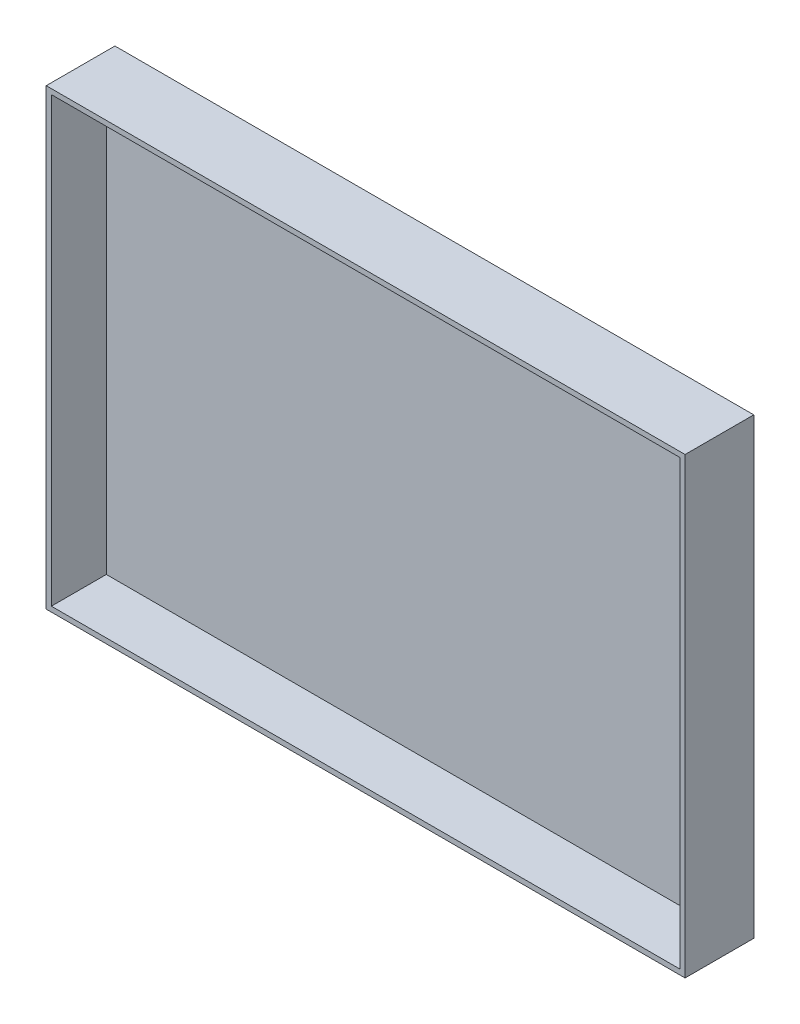
SolidWorks part; units mm, degrees
ref_plane "Front Plane" through (0, 0, 0) normal (0, 0, 1) x (1, 0, 0)
ref_plane "Top Plane" through (0, 0, 0) normal (0, 1, 0) x (1, 0, 0)
ref_plane "Right Plane" through (0, 0, 0) normal (1, 0, 0) x (0, 0, -1)
sketch "Sketch1" plane through (0, 0, 0) normal (0, 0, 1) x (1, 0, 0)
  line L1 (-45.75, -32.25) -> (45.75, -32.25)
  line L2 (-45.75, -32.25) -> (-45.75, 32.25)
  line L3 (-45.75, 32.25) -> (45.75, 32.25)
  line L4 (45.75, -32.25) -> (45.75, 32.25)
  line L5 (-45.75, -32.25) -> (45.75, 32.25) construction
  line L6 (-45.75, 32.25) -> (45.75, -32.25) construction
  line L7 (46.5, -33) -> (-46.5, -33)
  line L8 (46.5, -33) -> (46.5, 33)
  line L9 (46.5, 33) -> (-46.5, 33)
  line L10 (-46.5, -33) -> (-46.5, 33)
  line L11 (46.5, -33) -> (-46.5, 33) construction
  line L12 (46.5, 33) -> (-46.5, -33) construction
  point P0 (0, 0)
  point P6 (0, 0)
  dimension "D1" = 91.5
  dimension "D2" = 64.5
  dimension "D3" = 66
  dimension "D4" = 93
extrude "Boss-Extrude1" add sketch "Sketch1" along normal blind 10
sketch "Sketch2" plane through (0, 0, 0) normal (0, 0, 1) x (1, 0, 0)
  line L1 (-46.5, -33) -> (46.5, -33)
  line L2 (-46.5, -33) -> (-46.5, 33)
  line L3 (-46.5, 33) -> (46.5, 33)
  line L4 (46.5, -33) -> (46.5, 33)
  line L5 (-46.5, -33) -> (46.5, 33) construction
  line L6 (-46.5, 33) -> (46.5, -33) construction
  point P0 (0, 0)
extrude "Boss-Extrude2" add sketch "Sketch2" along normal blind 2
